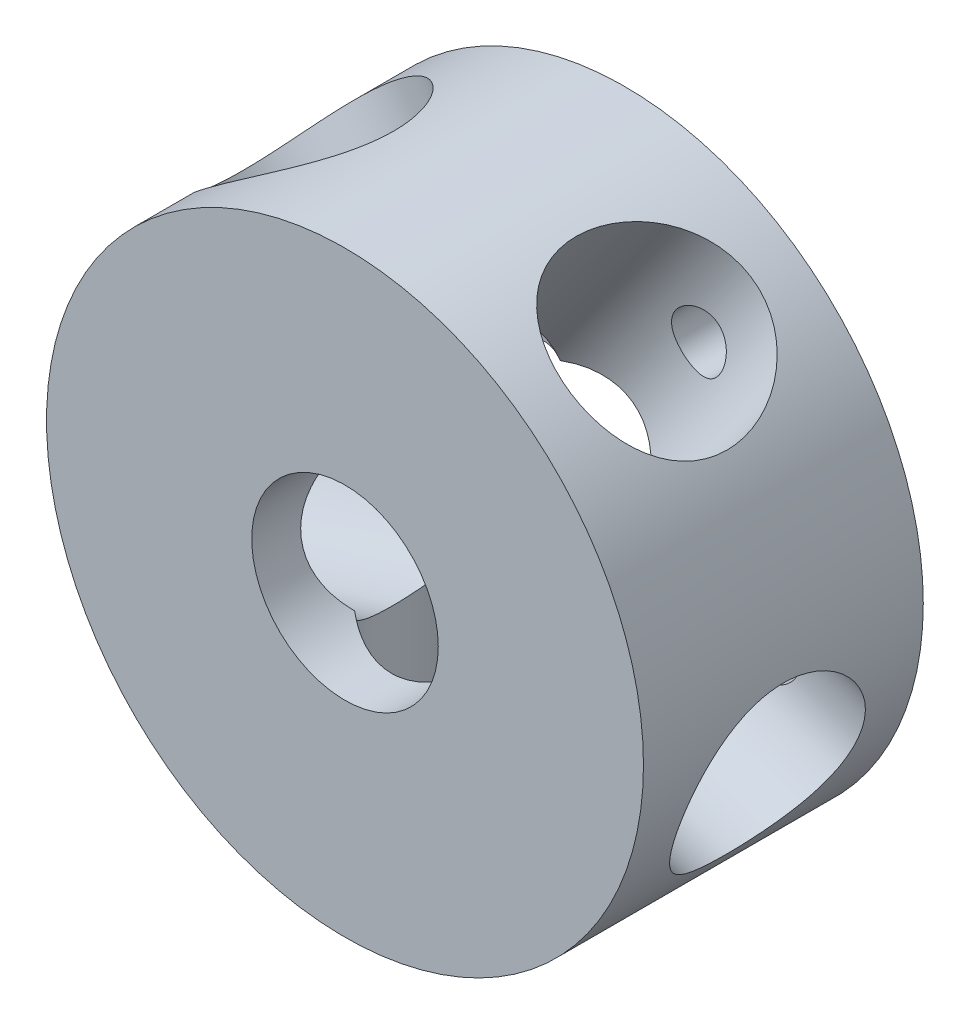
SolidWorks part; units mm, degrees
material "Plain Carbon Steel"
ref_plane "Front Plane" through (0, 0, 0) normal (0, 0, 1) x (1, 0, 0)
ref_plane "Top Plane" through (0, 0, 0) normal (0, 1, 0) x (1, 0, 0)
ref_plane "Right Plane" through (0, 0, 0) normal (1, 0, 0) x (0, 0, -1)
sketch "Sketch1" plane through (0, 0, 0) normal (0, 0, 1) x (1, 0, 0)
  circle A0 centre (0, 0) radius 32
  circle A1 centre (0, 0) radius 10
  dimension "D1" = 64
  dimension "D2" = 20
extrude "Boss-Extrude1" add sketch "Sketch1" along normal mid plane 30
sketch "Sketch2" plane through (0, 0, 0) normal (0, 1, 0) x (1, 0, 0)
  circle A0 centre (0, 0) radius 10
  dimension "D1" = 20
extrude "Cut-Extrude1" cut sketch "Sketch2" against normal through all
pattern_circular "CirPattern1" count 5 over 360 about axis through (0, 0, 15) along (0, 0, -1) of "Cut-Extrude1"
sketch "Sketch4" plane through (0, 0, -15) normal (0, 0, 1) x (1, 0, 0)
  line L0 (0, 0) -> (-18.3544, 26.2129) construction
  line L2 (0, 0) -> (-35.061, 0) construction
  line L3 (-18.3544, 26.2129) -> (-12.6187, 18.0213)
  circle A0 centre (0, 0) radius 32 construction
  circle A1 centre (-12.6187, 18.0213) radius 3
  dimension "D1" = 55
extrude "Cut-Extrude3" cut sketch "Sketch4" along normal blind 11 contours A1
pattern_circular "CirPattern2" count 5 over 360 about axis through (0, 0, 0) along (0, 0, 1) of "Cut-Extrude3"
